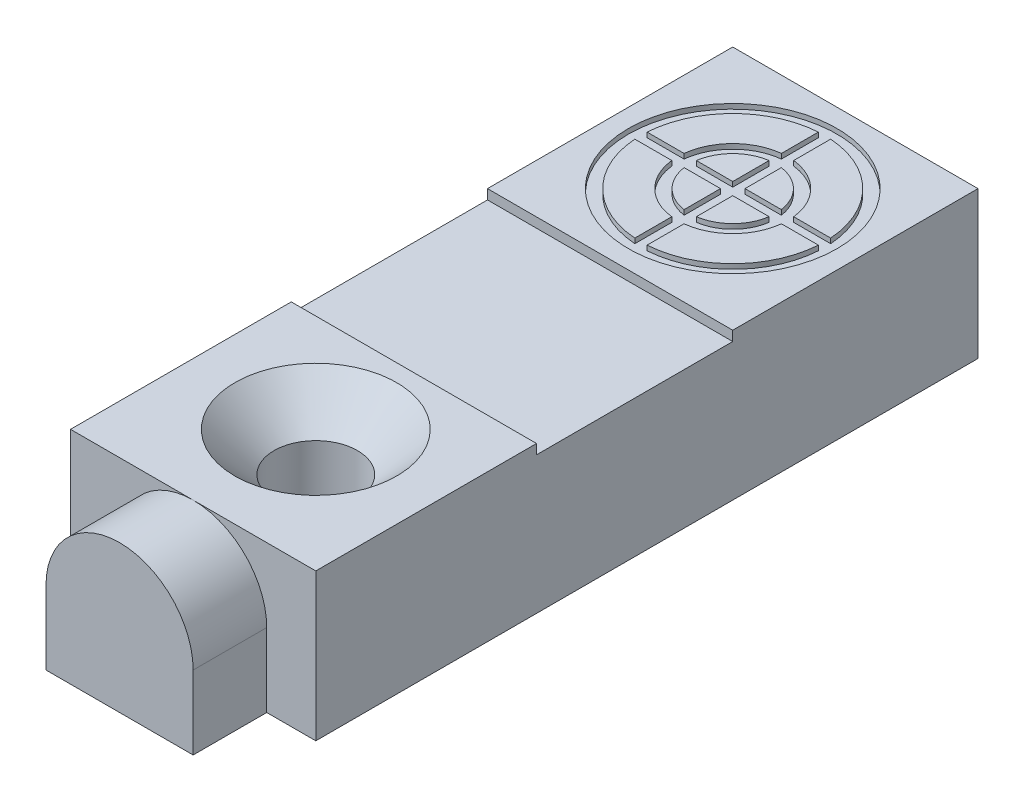
SolidWorks part; units mm, degrees
ref_plane "前视基准面" through (0, 0, 0) normal (0, 0, 1) x (1, 0, 0)
ref_plane "上视基准面" through (0, 0, 0) normal (0, 1, 0) x (1, 0, 0)
ref_plane "右视基准面" through (0, 0, 0) normal (1, 0, 0) x (0, 0, -1)
sketch "草图1" plane through (0, 0, 0) normal (0, 1, 0) x (1, 0, 0)
  line L1 (0, 0) -> (10, 0)
  line L2 (0, 0) -> (0, 27)
  line L3 (0, 27) -> (10, 27)
  line L4 (10, 0) -> (10, 27)
  circle A0 centre (5, 5) radius 1.5
  dimension "D5" = 3
  dimension "D1" = 27
  dimension "D2" = 10
  dimension "D3" = 5
  dimension "D4" = 5
extrude "凸台-拉伸1" add sketch "草图1" along normal blind 6
sketch "草图2" plane through (0, 6, 0) normal (0, 1, 0) x (1, 0, 0)
  line L0 (1, 22) -> (9, 22)
  line L1 (5, 26) -> (5, 18)
  line L2 (10, 27) -> (0, 27) construction
  line L3 (10, 0) -> (10, 27) construction
  circle A0 centre (5, 22) radius 2
  circle A1 centre (5, 22) radius 4
  dimension "D1" = 4
  dimension "D2" = 8
  dimension "D3" = 5
  dimension "D4" = 5
extrude "切除-拉伸-薄壁1" cut sketch "草图2" against normal blind 0.2 thin contours A0 | L1 | L0 | A1 thin type mid plane wall 0.5
sketch "草图3" plane through (0, 6, 0) normal (0, 1, 0) x (1, 0, 0)
  line L0 (0, 27) -> (0, 0) construction
  line L1 (0, 17) -> (10, 17)
  line L2 (0, 17) -> (0, 9)
  line L3 (0, 9) -> (10, 9)
  line L4 (10, 17) -> (10, 9)
  line L5 (10, 0) -> (10, 27) construction
  line L6 (10, 27) -> (0, 27) construction
  dimension "D1" = 8
  dimension "D2" = 10
extrude "切除-拉伸1" cut sketch "草图3" against normal blind 0.4
hole_wizard "打孔尺寸(%根据十字)槽半沉头木螺钉的类型1" positions "草图4" profile "草图5" countersink size "M3" standard "GB"
sketch "草图4" plane through (0, 6, 0) normal (0, 1, 0) x (1, 0, 0)
  point P0 (5, 5)
sketch "草图5" plane through (5, 6, -5) normal (1, 0, 0) x (0, 0, 1)
  line L0 (0, 0) -> (0, 23.2715)
  line L1 (0, 23.2715) -> (1.7, 22.25)
  line L2 (1.7, 22.25) -> (1.7, 1.6)
  line L3 (1.7, 1.6) -> (3.3, 0)
  line L5 (3.3, 0) -> (0, 0)
  line L6 (-1.7, 1.6) -> (-3.3, 0) construction
  line L10 (0, 23.2715) -> (-1.7, 22.25) construction
  line L11 (0, -6.35) -> (0, 107.95) construction
  dimension "孔直径" = 3.4
  dimension "孔深度" = 22.25
  dimension "近端锥形沉头孔直径" = 6.6
  dimension "近端锥形沉头孔角度" = 90
  dimension "导头角度" = 118
sketch "草图6" plane through (0, 0, 0) normal (0, 0, 1) x (1, 0, 0)
  line L0 (0, 0) -> (10, 0) construction
  line L1 (10, 6) -> (10, 0) construction
  line L2 (2, 3) -> (2, 0)
  line L3 (2, 0) -> (8, 0)
  line L4 (8, 0) -> (8, 3)
  arc A0 (8, 3) -> (2, 3) centre (5, 3) ccw
  dimension "D1" = 6
  dimension "D2" = 3
  dimension "D3" = 5
extrude "凸台-拉伸2" add sketch "草图6" along normal blind 3
